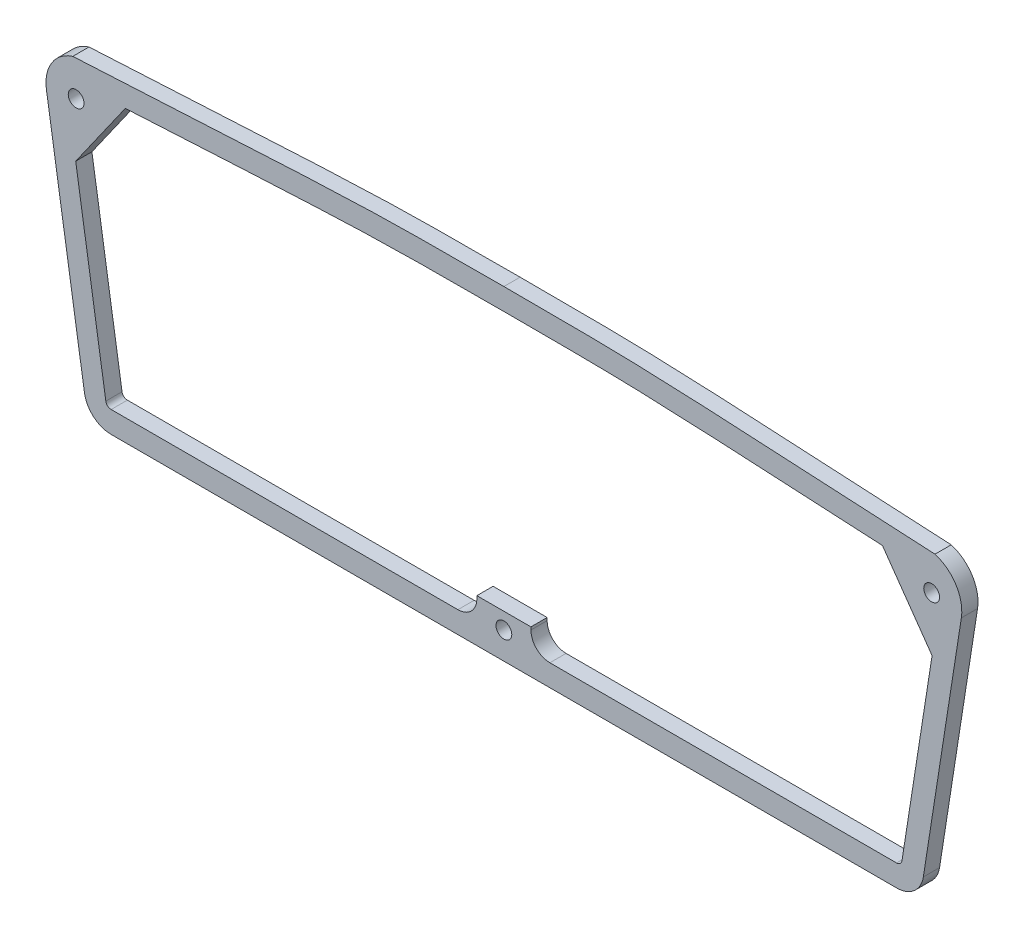
SolidWorks part; units mm, degrees
ref_plane "Alzado" through (0, 0, 0) normal (0, 0, 1) x (1, 0, 0)
ref_plane "Planta" through (0, 0, 0) normal (0, 1, 0) x (1, 0, 0)
ref_plane "Vista lateral" through (0, 0, 0) normal (1, 0, 0) x (0, 0, -1)
sketch "Croquis1" plane through (0, 0, 0) normal (0, 0, 1) x (1, 0, 0)
  line L0 (72.621, -42.7139) -> (-72.621, -42.7139)
  line L1 (79.7182, 14.2861) -> (-79.7182, 14.2861) construction
  line L2 (0, 14.2861) -> (0, 17.2861) construction
  line L3 (-77.7935, 17.2861) -> (77.7935, 17.2861) construction
  line L4 (0, -40.4126) -> (0, 34.1548) construction
  line L5 (-25, 41.2162) -> (-25, -46.3712) construction
  line L6 (-77.5611, -38.4855) -> (-84.5891, 6.5113)
  line L11 (25, 41.2162) -> (25, -46.3712) construction
  line L14 (77.5611, -38.4855) -> (84.5891, 6.5113)
  arc A0 (84.5891, 6.5113) -> (79.7182, 14.2861) centre (77.6729, 7.5915) ccw
  arc A1 (77.5611, -38.4855) -> (72.621, -42.7139) centre (72.621, -37.7139) cw
  arc A2 (-77.5611, -38.4855) -> (-72.621, -42.7139) centre (-72.621, -37.7139) ccw
  arc A3 (-84.5891, 6.5113) -> (-79.7182, 14.2861) centre (-77.6729, 7.5915) cw
  conic Q0 (79.7182, 14.2861) -> (0, 17.2861) control (25, 17.2861) rho 0.75
  conic Q1 (-79.7182, 14.2861) -> (0, 17.2861) control (-25, 17.2861) rho 0.75
  point P15 (-84.627, 12.5288)
  point P27 (0, -42.7139)
  point P28 (0, -42.7139)
  point P40 (0, 9.5288)
  point P61 (0, -42.7139)
  point P62 (84.627, 12.5288)
  dimension "D1" = 5
  dimension "D2" = 7
  dimension "D4" = 60
  dimension "D3" = 3
extrude "Saliente-Extruir3" add sketch "Croquis1" along normal blind 3 contours Q0 Q1 A3 L6 A2 L0 A1 L14 A0
sketch "Croquis10" plane through (0, 0, 0) normal (0, 0, -1) x (-1, 0, 0)
  line L0 (-79.1761, -2.225) -> (-70, 10.8116)
  line L1 (79.1761, -2.225) -> (70, 10.8116)
  line L2 (5, -34.7139) -> (-5, -34.7139)
  line L3 (-89.1533, -2.1273) -> (92.9339, -3.91) construction
  line L4 (-70, 32.4884) -> (-70, -57.6963) construction
  line L5 (70, -55.635) -> (70, -62.635) construction
  line L6 (-80.637, 7.1286) -> (-73.609, -37.8682)
  line L7 (-72.621, -38.7139) -> (72.621, -38.7139)
  line L8 (73.609, -37.8682) -> (80.637, 7.1286)
  line L9 (-79.1761, -2.225) -> (-73.609, -37.8682)
  line L10 (-72.621, -38.7139) -> (-8.5, -38.7139)
  line L11 (73.609, -37.8682) -> (79.1761, -2.225)
  line L12 (0, -66.0706) -> (0, -38.7139) construction
  line L13 (-5, -34.7139) -> (-5, -35.2139)
  line L14 (5, -34.7139) -> (5, -35.2139)
  line L15 (-72.621, -42.7139) -> (72.621, -42.7139) construction
  line L16 (8.5, -38.7139) -> (72.621, -38.7139)
  line L17 (0, -34.7139) -> (0, 45.5866) construction
  line L18 (2.4598, -37.7139) -> (-1.8908, -37.7139) construction
  arc A0 (-5, -35.2139) -> (-8.5, -38.7139) centre (-8.5, -35.2139) cw
  arc A1 (8.5, -38.7139) -> (5, -35.2139) centre (8.5, -35.2139) cw
  arc A8 (-78.9106, 10.3243) -> (-80.637, 7.1286) centre (-77.6729, 7.5915) ccw
  arc A9 (-73.609, -37.8682) -> (-72.621, -38.7139) centre (-72.621, -37.7139) ccw
  arc A10 (72.621, -38.7139) -> (73.609, -37.8682) centre (72.621, -37.7139) ccw
  arc A11 (80.637, 7.1286) -> (78.9106, 10.3243) centre (77.6729, 7.5915) ccw
  arc A13 (-73.609, -37.8682) -> (-72.621, -38.7139) centre (-72.621, -37.7139) ccw
  arc A14 (72.621, -38.7139) -> (73.609, -37.8682) centre (72.621, -37.7139) ccw
  spline S4 degree 3 poles (1861.8129, 2143.982) (1179.9403, -85.7608) (620.546, -18.8298) (52.6222, 11.7513) (46.0499, 12.1034) (36.1891, 12.5892) (32.9019, 12.7438) (26.3256, 13.0031) (23.0364, 13.1028) (16.455, 13.2247) (13.1641, 13.2517) (-226.8331, 14.3729) (-463.9176, -45.496) (-682.4542, 2884.5734) knots -21.1031 -21.1031 -21.1031 -21.1031 0.25 0.25 0.5 0.5 0.625 0.625 0.75 0.75 0.875 0.875 9.865729 9.865729 9.865729 9.865729 only from (78.9106, 10.3243) to (0, 13.2861)
  spline S5 degree 3 poles (682.51, 2884.5512) (463.9152, -45.4957) (226.8325, 14.3729) (-13.1641, 13.2517) (-16.455, 13.2247) (-23.0364, 13.1028) (-26.3256, 13.0031) (-32.9019, 12.7438) (-36.1891, 12.5892) (-46.0499, 12.1034) (-52.6222, 11.7513) (-620.5466, -18.8298) (-1179.9416, -85.761) (-1861.805, 2143.9895) knots -8.865702 -8.865702 -8.865702 -8.865702 0.125 0.125 0.25 0.25 0.375 0.375 0.5 0.5 0.75 0.75 22.103123 22.103123 22.103123 22.103123 only from (0, 13.2861) to (-78.9106, 10.3243)
  spline S6 degree 3 poles (70, 10.8116) (66.3982, 11.008) (62.7964, 11.2034) (52.6222, 11.7513) (46.0499, 12.1034) (36.1891, 12.5892) (32.9019, 12.7438) (26.3256, 13.0031) (23.0364, 13.1028) (16.455, 13.2247) (13.1641, 13.2517) (6.5821, 13.2825) (3.2911, 13.2861) (0, 13.2861) knots 0.112988 0.112988 0.112988 0.112988 0.25 0.25 0.5 0.5 0.625 0.625 0.75 0.75 0.875 0.875 1 1 1 1
  spline S7 degree 3 poles (0, 13.2861) (-3.2911, 13.2861) (-6.5821, 13.2825) (-13.1641, 13.2517) (-16.455, 13.2247) (-23.0364, 13.1028) (-26.3256, 13.0031) (-32.9019, 12.7438) (-36.1891, 12.5892) (-46.0499, 12.1034) (-52.6222, 11.7513) (-62.7964, 11.2034) (-66.3982, 11.008) (-70, 10.8116) knots 0 0 0 0 0.125 0.125 0.25 0.25 0.375 0.375 0.5 0.5 0.75 0.75 0.887012 0.887012 0.887012 0.887012
  point P8 (-79.1761, -2.225)
  point P9 (-70, 10.8116)
  point P40 (5, -38.7139)
  point P43 (0, -37.7139)
  point P46 (-0.1687, -34.7139)
  dimension "D8" = 3.5
  dimension "D2" = 70
  dimension "D3" = 70
  dimension "D4" = 3
  dimension "D5" = 8
  dimension "D6" = 5
  dimension "D7" = 5
  dimension "D9" = 5
  dimension "D1" = 4
extrude "Cortar-Extruir2" cut sketch "Croquis10" against normal blind 3
sketch "Croquis11" plane through (0, 0, 0) normal (0, 0, -1) x (-1, 0, 0)
  line L0 (-74.588, 4.2933) -> (-83.6049, 11.3079) construction
  line L1 (-70, 10.8116) -> (-79.1761, -2.225) construction
  line L2 (74.588, 4.2933) -> (83.6049, 11.3079) construction
  line L3 (79.1761, -2.225) -> (70, 10.8116) construction
  line L4 (0, 0) -> (0, -72.0529) construction
  line L5 (4.267, -37.7139) -> (-4.5681, -37.7139) construction
  line L6 (-72.621, -42.7139) -> (72.621, -42.7139) construction
  arc A0 (-79.7182, 14.2861) -> (-84.5891, 6.5113) centre (-77.6729, 7.5915) ccw construction
  arc A1 (84.5891, 6.5113) -> (79.7182, 14.2861) centre (77.6729, 7.5915) ccw construction
  point P14 (79.0965, 7.8006)
  point P15 (-79.0965, 7.8006)
  point P23 (0, -37.7139)
  dimension "D1" = 5
hole_wizard "Taladro de margen para #32" positions "Croquis3D1" profile "Croquis12" hole size "#3" standard "Ansi Inch" end condition through all
sketch3d "Croquis3D1"
  point P0 (79.0965, 7.8006, 0)
  point P3 (-79.0965, 7.8006, 0)
sketch "Croquis12" plane through (79.0965, 7.8006, 0) normal (1, 0, 0) x (0, 1, 0)
  line L0 (0, 0) -> (0, 3.01)
  line L1 (0, 3.01) -> (1.4605, 3.01)
  line L2 (1.4605, 3.01) -> (1.4605, 0)
  line L5 (1.4605, 0) -> (0, 0)
  line L11 (0, -6.35) -> (0, 107.95) construction
  dimension "Diámetro de taladro hasta el siguiente" = 2.921
  dimension "Profundidad de taladro hasta el siguiente" = 3.01
hole_wizard "Taladro de margen para #33" positions "Croquis3D6" profile "Croquis17" hole size "#3" standard "Ansi Inch" end condition through all
sketch3d "Croquis3D6"
  point P0 (0, -37.7139, 0)
sketch "Croquis17" plane through (0, -37.7139, 0) normal (1, 0, 0) x (0, 1, 0)
  line L0 (0, 0) -> (0, 3.01)
  line L1 (0, 3.01) -> (1.4605, 3.01)
  line L2 (1.4605, 3.01) -> (1.4605, 0)
  line L5 (1.4605, 0) -> (0, 0)
  line L11 (0, -6.35) -> (0, 107.95) construction
  dimension "Diámetro de taladro hasta el siguiente" = 2.921
  dimension "Profundidad de taladro hasta el siguiente" = 3.01
